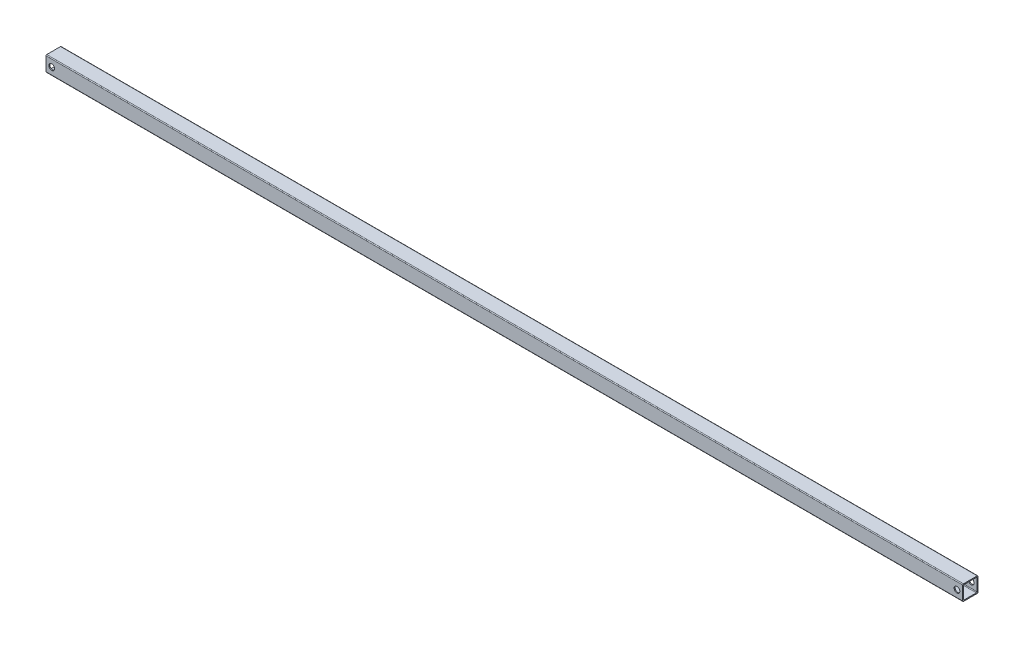
SolidWorks part; units mm, degrees
ref_plane "Front" through (0, 0, 0) normal (0, 0, 1) x (1, 0, 0)
ref_plane "Top" through (0, 0, 0) normal (0, 1, 0) x (1, 0, 0)
ref_plane "Right" through (0, 0, 0) normal (1, 0, 0) x (0, 0, -1)
sketch "Sketch1" plane through (0, 0, 0) normal (1, 0, 0) x (0, 0, -1)
  line L0 (-11.049, 0) -> (-12.7, 0) construction
  line L1 (11.43, -12.7) -> (-11.43, -12.7) construction
  line L2 (12.7, -11.43) -> (12.7, 11.43) construction
  line L3 (11.43, 12.7) -> (-11.43, 12.7) construction
  line L4 (-12.7, -11.43) -> (-12.7, 11.43) construction
  line L5 (12.7, -12.7) -> (-12.7, 12.7) construction
  line L6 (12.7, 12.7) -> (-12.7, -12.7) construction
  line L7 (9.9441, 11.049) -> (-9.9441, 11.049) construction
  line L8 (11.049, 9.9441) -> (11.049, -9.9441) construction
  line L9 (9.9441, -11.049) -> (-9.9441, -11.049) construction
  line L10 (-11.049, 9.9441) -> (-11.049, -9.9441) construction
  line L11 (11.049, 11.049) -> (-11.049, -11.049) construction
  line L12 (11.049, -11.049) -> (-11.049, 11.049) construction
  line L13 (0, -11.049) -> (0, -12.7) construction
  line L14 (11.049, -9.9441) -> (11.049, -12.7) construction
  line L15 (11.049, 0) -> (12.7, 0) construction
  line L16 (11.049, -12.7) -> (12.7, -12.7) construction
  arc A0 (-9.9441, -11.049) -> (-11.049, -9.9441) centre (-9.9441, -9.9441) cw construction
  arc A1 (11.049, -9.9441) -> (9.9441, -11.049) centre (9.9441, -9.9441) cw construction
  arc A2 (9.9441, 11.049) -> (11.049, 9.9441) centre (9.9441, 9.9441) cw construction
  arc A3 (-9.9441, 11.049) -> (-11.049, 9.9441) centre (-9.9441, 9.9441) ccw construction
  arc A4 (11.43, -12.7) -> (12.7, -11.43) centre (11.43, -11.43) ccw construction
  arc A5 (12.7, 11.43) -> (11.43, 12.7) centre (11.43, 11.43) ccw construction
  arc A6 (-11.43, 12.7) -> (-12.7, 11.43) centre (-11.43, 11.43) ccw construction
  arc A7 (-11.43, -12.7) -> (-12.7, -11.43) centre (-11.43, -11.43) cw construction
  point P0 (0, 0)
  point P6 (0, 0)
  dimension "D2" = 1.1049
  dimension "D3" = 1.27
  dimension "Outside Width" = 25.4
  dimension "Ouside Height" = 25.4
  dimension "Inside Height" = 22.098
  dimension "Wall Thickness" = 1.651
sketch "Sketch2" plane through (0, 0, 0) normal (0, 0, 1) x (1, 0, 0)
  line L0 (-762, 0) -> (762, 0) construction
  point P3 (-738.251, 0)
  point P4 (738.251, 0)
  dimension "Length" = 1524
  dimension "D1" = 23.749
  dimension "D2" = 23.749
sketch "Sketch4" plane through (0, 0, 0) normal (1, 0, 0) x (0, 0, -1)
  line L8 (12.7, -11.43) -> (12.7, 11.43)
  line L9 (11.43, 12.7) -> (-11.43, 12.7)
  line L10 (-12.7, -11.43) -> (-12.7, 11.43)
  line L11 (11.43, -12.7) -> (-11.43, -12.7)
  line L12 (11.049, 9.9441) -> (11.049, -9.9441)
  line L13 (9.9441, -11.049) -> (-9.9441, -11.049)
  line L14 (-11.049, 9.9441) -> (-11.049, -9.9441)
  line L15 (9.9441, 11.049) -> (-9.9441, 11.049)
  arc A8 (12.7, 11.43) -> (11.43, 12.7) centre (11.43, 11.43) ccw
  arc A9 (-11.43, 12.7) -> (-12.7, 11.43) centre (-11.43, 11.43) ccw
  arc A10 (-12.7, -11.43) -> (-11.43, -12.7) centre (-11.43, -11.43) ccw
  arc A11 (11.43, -12.7) -> (12.7, -11.43) centre (11.43, -11.43) ccw
  arc A12 (9.9441, -11.049) -> (11.049, -9.9441) centre (9.9441, -9.9441) ccw
  arc A13 (-11.049, -9.9441) -> (-9.9441, -11.049) centre (-9.9441, -9.9441) ccw
  arc A14 (-9.9441, 11.049) -> (-11.049, 9.9441) centre (-9.9441, 9.9441) ccw
  arc A15 (11.049, 9.9441) -> (9.9441, 11.049) centre (9.9441, 9.9441) ccw
extrude "Boss-Extrude1" add sketch "Sketch4" along normal up to vertex (762 mm away) and the other way up to vertex (762 mm away)
sketch "Sketch6" plane through (0, 0, 12.7) normal (0, 0, 1) x (1, 0, 0)
  line L0 (762, 11.43) -> (762, -11.43) construction
  line L1 (762, 12.7) -> (-762, 12.7) construction
  line L2 (-762, 11.43) -> (-762, -11.43) construction
  circle A0 centre (752.475, 0) radius 4.7625
  circle A1 centre (-752.475, 0) radius 4.7625
  dimension "D1" = 9.525
  dimension "D2" = 9.525
  dimension "D3" = 12.7
  dimension "D4" = 9.525
  dimension "D5" = 12.7
  dimension "D6" = 9.525
extrude "Cut-Extrude1" cut sketch "Sketch6" against normal through all
equation "\"D3@Sketch1\"=\"Outside Width@Sketch1\"*.05"
equation "\"D2@Sketch1\" = \"Inside Height@Sketch1\" * .05"
equation "\"D1@Sketch2\"=\"Outside Width@Sketch1\"-\"Wall Thickness@Sketch1\""
equation "\"D2@Sketch2\"=\"D1@Sketch2\""
